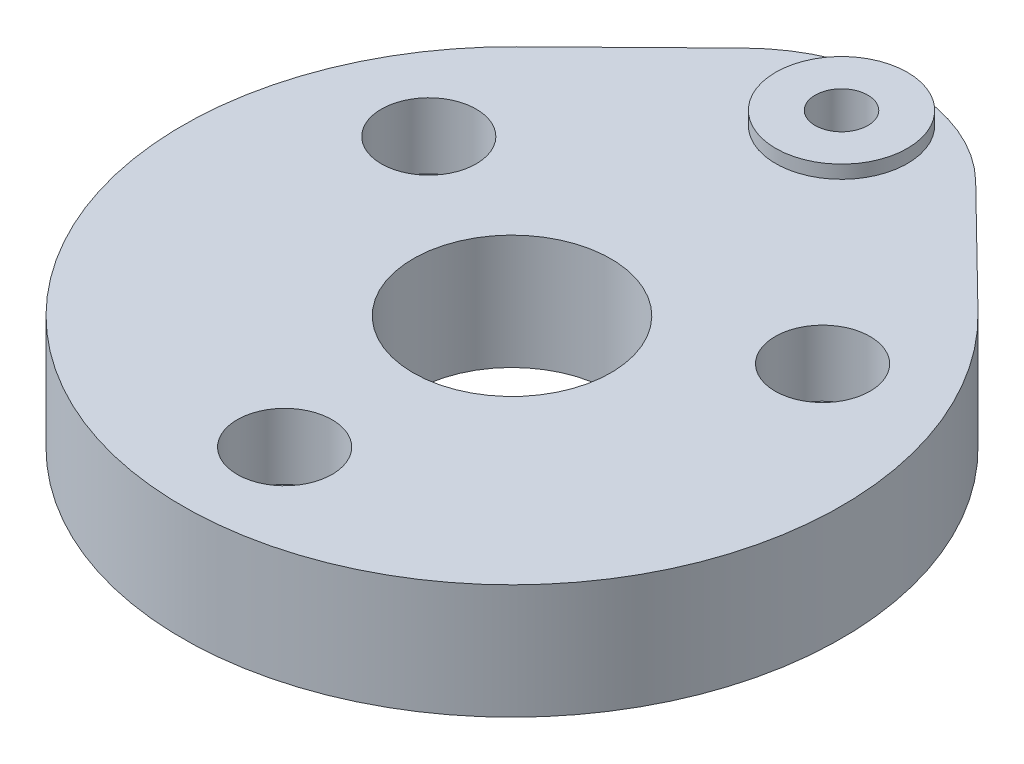
SolidWorks part; units mm, degrees
ref_plane "前视基准面" through (0, 0, 0) normal (0, 0, 1) x (1, 0, 0)
ref_plane "上视基准面" through (0, 0, 0) normal (0, 1, 0) x (1, 0, 0)
ref_plane "右视基准面" through (0, 0, 0) normal (1, 0, 0) x (0, 0, -1)
other "Configuration Table"
sketch "草图1" plane through (0, 0, 0) normal (0, 1, 0) x (1, 0, 0)
  line L0 (0, 0) -> (14.9389, 8.625) construction
  line L1 (0, 0) -> (18.7484, 0) construction
  circle A0 centre (0, 0) radius 25
  circle A1 centre (14.9389, 8.625) radius 1.9
  circle A2 centre (0, -17.25) radius 1.9
  circle A3 centre (-14.9389, 8.625) radius 1.9
  circle A7 centre (0, 0) radius 7.5
  point P17 (0, 0)
  dimension "D1" = 50
  dimension "D2" = 3.8
  dimension "D5" = 15
  dimension "D6" = 30
  dimension "D3" = 17.25
  dimension "D4" = 3
extrude "凸台-拉伸1" add sketch "草图1" along normal blind 8.7
sketch "草图2" plane through (0, 8.7, 0) normal (0, 1, 0) x (1, 0, 0)
  circle A18 centre (0, -17.25) radius 3.6
  circle A19 centre (-14.9389, 8.625) radius 3.6
  circle A20 centre (14.9389, 8.625) radius 3.6
  dimension "D1" = 7.2
extrude "切除-拉伸1" cut sketch "草图2" against normal blind 5
sketch "草图13" plane through (0, 8.7, 0) normal (0, 1, 0) x (1, 0, 0)
  line L0 (-17.4964, 17.8571) -> (-8.7482, 26.4286)
  line L1 (8.7482, 26.4286) -> (17.4964, 17.8571)
  circle A0 centre (0, 25) radius 2
  arc A1 (-8.7482, 26.4286) -> (8.7482, 26.4286) centre (0, 17.5) cw
  circle A2 centre (0, 0) radius 25
  circle A3 centre (0, 0) radius 25
  circle A4 centre (0, 25) radius 5 construction
  point P13 (0, 35)
  dimension "D2" = 4
  dimension "D5" = 10
  dimension "D4" = 35
  dimension "D1" = 25
  dimension "D3" = 0
extrude "凸台-拉伸4" add sketch "草图13" against normal up to surface (8.7 mm away) up to face at (0, 0, 25)
sketch "草图14" plane through (0, 8.7, 0) normal (0, 1, 0) x (1, 0, 0)
  circle A0 centre (0, 25) radius 2
  point P2 (0, 0)
  dimension "D1" = 4
  dimension "D2" = 25
extrude "切除-拉伸5" cut sketch "草图14" against normal through all
sketch "草图15" plane through (0, 8.7, 0) normal (0, 1, 0) x (1, 0, 0)
  circle A0 centre (0, 25) radius 5
  circle A1 centre (0, 25) radius 2 construction
  circle A2 centre (0, 25) radius 2
  dimension "D1" = 10
extrude "凸台-拉伸5" add sketch "草图15" along normal blind 1
sketch "草图19" plane through (0, 0, 0) normal (0, -1, 0) x (1, 0, 0)
  circle A2 centre (0, -25) radius 3.75
  dimension "D1" = 7.5
extrude "切除-拉伸7" cut sketch "草图19" against normal blind 2.7
